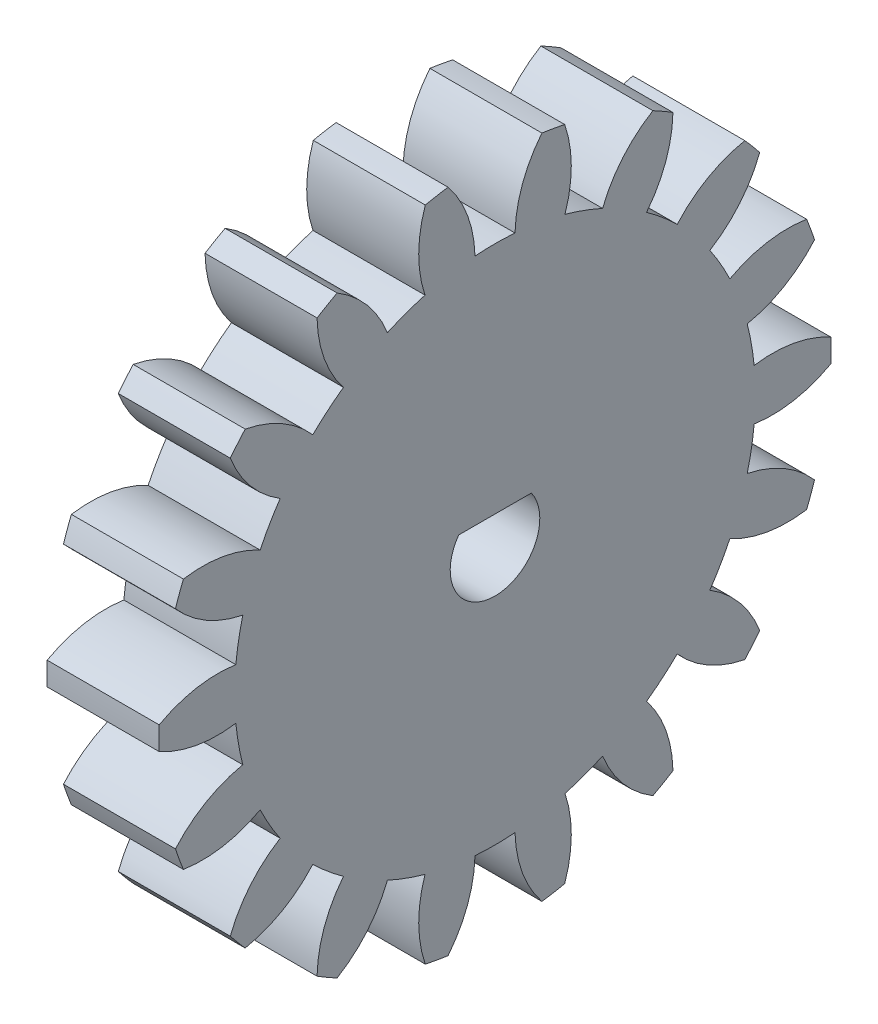
SolidWorks part; units mm, degrees
ref_plane "Plane1" through (0, 0, 0) normal (0, 0, 1) x (1, 0, 0)
ref_plane "Plane2" through (0, 0, 0) normal (0, 1, 0) x (1, 0, 0)
ref_plane "Plane3" through (0, 0, 0) normal (1, 0, 0) x (0, 0, -1)
sketch "HoldingSke" plane through (0, 0, 0) normal (0, 1, 0) x (1, 0, 0)
  line L0 (0, 0) -> (0.634, -0.206)
  line L1 (-15, 0) -> (100, 0) construction
  line L2 (0, 0) -> (-2.1039, 2.3779)
  line L3 (0, 0) -> (-11.863, 4.5341)
  line L4 (0, 0) -> (8.2133, 2.6687)
  line L5 (0, 0) -> (-46.8476, -17.4728)
  line L6 (0, 0) -> (-4.1448, -2.7965)
  line L7 (-2.1039, 2.3779) -> (8.6586, 51.2059)
  line L8 (-76.2, 54.61) -> (-76.1, 54.61)
  line L9 (-67.7845, 28.3722) -> (-49.3413, 33.142)
  line L10 (-76.2, 71.12) -> (104.1128, 71.12)
  line L11 (0, 0) -> (-5, 0)
  line L12 (-76.2, 101.6) -> (-76.147, 101.6)
  line L13 (24.9733, 27.94) -> (52.9518, 28.4284)
  line L14 (24.9733, 27.94) -> (24.9743, 27.94)
  line L15 (24.9733, 27.94) -> (100.4006, 29.5858)
  line L16 (-63.627, -1.5) -> (-12.827, -1.5)
  circle A0 centre (0, 0) radius 0.4
  circle A1 centre (0, 0) radius 11.624
  circle A2 centre (0, 0) radius 37.5
  circle A3 centre (0, 0) radius 0.4
  dimension "MHD" = 23.248
  dimension "Hub_dia" = 75
  dimension "Bore" = 0.8
  dimension "MBD" = 0.8
  dimension "Num_teeth" = 18
  dimension "Pitch" = 0.6667
  dimension "Overall_len" = 50
  dimension "Show_teeth" = 18
  dimension "Thickness" = 5
  dimension "OAL" = 50.0001
  dimension "T_dim" = 0.1
  dimension "Ap" = 14.5
  dimension "H" = 19.05
  dimension "Pitch_radius" = 180.3128
  dimension "Width" = 5
  dimension "Backlash" = 0.053
  dimension "Addendum_fac" = 1
  dimension "Dedendum_fac" = 1.25
  dimension "Clearance_fac" = 0.25
  dimension "Dedendum_add" = 0.001
  dimension "Module" = 1.5
sketch "BasProSke" plane through (0, 0, 0) normal (0, 1, 0) x (1, 0, 0)
  line L0 (-10, 0) -> (60, 0) construction
  line L1 (0, 0) -> (0, 15)
  line L2 (0, 0) -> (5, 0)
  line L3 (5, 0) -> (5, 15)
  line L4 (5, 15) -> (0, 15)
  dimension "Thickness" = 5
  dimension "Diameter" = 30
revolve "Base-Revolve" add sketch "BasProSke" angle 360 about L0
sketch "TooCutSke" plane through (0, 0, 0) normal (1, 0, 0) x (0, 0, -1)
  line L1 (0, 0) -> (0, 107) construction
  line L2 (0, 0) -> (-1.2693, 13.4402) construction
  line L3 (0, 0) -> (-4.6734, 26.504) construction
  line L4 (-1.2693, 13.4402) -> (-2.3367, 13.252) construction
  arc A0 (0.8932, 11.5896) -> (-0.8932, 11.5896) centre (0, 0) ccw
  arc A1 (2.1127, 14.8761) -> (-2.1127, 14.8761) centre (0, 0) ccw
  circle A2 centre (0, 0) radius 13.5 construction
  circle A3 centre (0, 0) radius 13.07 construction
  arc A4 (-0.8932, 11.5896) -> (-2.1127, 14.8761) centre (-6.2916, 11.456) ccw
  arc A5 (2.1127, 14.8761) -> (0.8932, 11.5896) centre (6.2916, 11.456) ccw
  dimension "Root_dia" = 23.248
  dimension "Overcut_dia" = 30.0508
  dimension "Pitch_dia" = 27
  dimension "Base_dia" = 26.14
  dimension "Flank_rad" = 5.4
  dimension "Half_ang" = 10
  dimension "Half_CT" = 1.0839
extrude "ToothCut" cut sketch "TooCutSke" along normal through all
fillet "Breaks" [suppressed] radius 0.03
fillet "RootFillets" [suppressed] radius 0.376
pattern_circular "TeethCuts" count 18 every 20 about axis through (-10, 0, 0) along (1, 0, 0) of "ToothCut", "RootFillets", "Breaks"
sketch "HubNeaOneSke" plane through (0, 0, 0) normal (-1, 0, 0) x (0, 0, 1)
  circle A0 centre (0, 0) radius 11.624
  dimension "Diameter" = 23.248
extrude "HubNearOne" [suppressed] add sketch "HubNeaOneSke" along normal blind 45.0001
sketch "HubNeaBotSke" plane through (0, 0, 0) normal (-1, 0, 0) x (0, 0, 1)
  circle A0 centre (0, 0) radius 11.624
  dimension "Diameter" = 23.248
extrude "HubNearBoth" [suppressed] add sketch "HubNeaBotSke" along normal blind 22.5
ref_plane "FarPln" through (5, 0, 0) normal (1, 0, 0) x (0, 0, -1)
sketch "HubFarSke" plane through (5, 0, 0) normal (1, 0, 0) x (0, 0, -1)
  circle A0 centre (0, 0) radius 11.624
  dimension "Diameter" = 23.248
extrude "HubFar" [suppressed] add sketch "HubFarSke" along normal blind 22.5
sketch "BorSke" plane through (0, 0, 0) normal (1, 0, 0) x (0, 0, -1)
  circle A0 centre (0, 0) radius 0.4
  dimension "Diameter" = 0.8
extrude "Bore" cut sketch "BorSke" along normal mid plane 100.0001
sketch "KeySke" plane through (0, 0, 0) normal (1, 0, 0) x (0, 0, -1)
  line L0 (-0.05, 0) -> (-0.05, 0.5)
  line L1 (-0.05, 0.5) -> (0.05, 0.5)
  line L2 (0.05, 0.5) -> (0.05, 0)
  line L3 (0, 0) -> (0, 34) construction
  line L4 (-0.05, 0) -> (0.05, 0)
  dimension "Offset" = 0.5
  dimension "Width" = 0.1
extrude "Keyway" [suppressed] cut sketch "KeySke" along normal mid plane 100.0001
pattern_circular "Keyway2" [suppressed] count 2 every 90 about axis through (-10, 0, 0) along (1, 0, 0)
sketch "Sketch1" plane through (5, 0, 0) normal (1, 0, 0) x (0, 0, -1)
  line L0 (-1.6209, 1.1716) -> (1.6209, 1.1716)
  circle A0 centre (0, 0) radius 2
extrude "Cut-Extrude1" cut sketch "Sketch1" against normal through all contours L0 A0
equation "' \"Module@HoldingSke\" = 6.35"
equation "' \"Num_teeth@HoldingSke\" = 12"
equation "' \"Ap@HoldingSke\" =  20"
equation "' \"Ap@HoldingSke\" = 20"
equation "' \"Width@HoldingSke\" = 0.5 * 25.4"
equation "' \"Hub_dia@HoldingSke\"= 1 * 25.4"
equation "' \"Hub_dia@HoldingSke\" = 1 * 25.4"
equation "' \"Overall_len@HoldingSke\" = 1.0 * 25.4"
equation "' \"Bore@HoldingSke\" = 0.75 * 25.4"
equation "' \"T_dim@HoldingSke\" = 0.1 * 25.4"
equation "' \"Width@KeySke\" = 0.25 * 25.4"
equation "' \"Show_teeth@HoldingSke\" = 13"
equation "' \"Backlash@HoldingSke\" = 0.009 * 25.4"
equation "' \"Addendum_fac@HoldingSke\" = 1.0"
equation "' \"Dedendum_fac@HoldingSke\" = 1.25"
equation "' \"Dedendum_add@HoldingSke\" = 0.00005 * 25.4"
equation "' \"Clearance_fac@HoldingSke\" = 0.25"
equation "\"Pitch@HoldingSke\" = 1 / \"Module@HoldingSke\""
equation "\"Overcut_dia@TooCutSke\" = (\"Num_teeth@HoldingSke\" + 2 * \"Addendum_fac@HoldingSke\") / \"Pitch@HoldingSke\" + 0.002 * 25.4"
equation "\"Pitch_dia@TooCutSke\" = \"Num_teeth@HoldingSke\" / \"Pitch@HoldingSke\""
equation "\"Base_dia@TooCutSke\" = \"Num_teeth@HoldingSke\" / \"Pitch@HoldingSke\" * cos((\"Ap@HoldingSke\"  * 3.14159265 / 180))"
equation "\"Root_dia@TooCutSke\" = (\"Num_teeth@HoldingSke\" + 2) / \"Pitch@HoldingSke\" - 2 * (\"Addendum_fac@HoldingSke\" + \"Dedendum_fac@HoldingSke\") / \"Pitch@HoldingSke\" - \"Dedendum_add@HoldingSke\" * 2"
equation "\"Half_ang@TooCutSke\" = 180 / \"Num_teeth@HoldingSke\""
equation "\"Half_CT@TooCutSke\" = \"Num_teeth@HoldingSke\" / \"Pitch@HoldingSke\" * sin((3.14159265 / 2 / \"Num_teeth@HoldingSke\")) / 2 - 7 * \"Backlash@HoldingSke\" / 4"
equation "\"Flank_rad@TooCutSke\" = \"Num_teeth@HoldingSke\" / \"Pitch@HoldingSke\" / 5"
equation "\"Radius@RootFillets\" = \"Clearance_fac@HoldingSke\" / \"Pitch@HoldingSke\" + \"Dedendum_add@HoldingSke\""
equation "\"Break_rad@Breaks\" = 0.02 / \"Pitch@HoldingSke\""
equation "\"Thickness@HoldingSke\" = \"Width@HoldingSke\""
equation "\"OAL@HoldingSke\" = \"Thickness@HoldingSke\""
equation "\"MHD@HoldingSke\" = (\"Num_teeth@HoldingSke\" + 2) / \"Pitch@HoldingSke\" - 2 * (\"Addendum_fac@HoldingSke\" + \"Dedendum_fac@HoldingSke\")  / \"Pitch@HoldingSke\" - \"Dedendum_add@HoldingSke\" * 2"
equation "\"MBD@HoldingSke\" = (\"Num_teeth@HoldingSke\" + 2) / \"Pitch@HoldingSke\" - 2 * (\"Addendum_fac@HoldingSke\" + \"Dedendum_fac@HoldingSke\")  / \"Pitch@HoldingSke\" - \"Dedendum_add@HoldingSke\" * 2 - 0.002 * 25.4"
equation "\"MHD@HoldingSke\" = ((sgn( \"MHD@HoldingSke\" - \"Hub_dia@HoldingSke\" )-1)*( \"MHD@HoldingSke\" - \"Hub_dia@HoldingSke\" ))/-2+ \"Hub_dia@HoldingSke\""
equation "\"MBD@HoldingSke\" = ((sgn( \"MBD@HoldingSke\" - \"Bore@HoldingSke\" )-1)*( \"MBD@HoldingSke\" - \"Bore@HoldingSke\" ))/-2+ \"Bore@HoldingSke\""
equation "\"OAL@HoldingSke\" = ((sgn( \"OAL@HoldingSke\" - \"Overall_len@HoldingSke\" )+1)*( \"OAL@HoldingSke\" - \"Overall_len@HoldingSke\" ))/2 + \"Overall_len@HoldingSke\" + 0.000002 * 25.4"
equation "\"Num_teeth@TeethCuts\" = int( \"Show_teeth@HoldingSke\" ) + 1"
equation "\"Num_teeth@TeethCuts\" = ((sgn( \"Num_teeth@TeethCuts\" - \"Num_teeth@HoldingSke\" )-1)*( \"Num_teeth@TeethCuts\" - \"Num_teeth@HoldingSke\" ))/-2+ \"Num_teeth@HoldingSke\""
equation "\"Num_teeth@TeethCuts\" = ((sgn( \"Num_teeth@TeethCuts\" - 2.0)+1)*( \"Num_teeth@TeethCuts\" - 2.0))/2 +2.0"
equation "\"Angle@TeethCuts\" = 360.0 / \"Num_teeth@HoldingSke\""
equation "\"Diameter@BasProSke\" = (\"Num_teeth@HoldingSke\" + 2 * \"Addendum_fac@HoldingSke\") / \"Pitch@HoldingSke\""
equation "\"Thickness@BasProSke\"  = \"Thickness@HoldingSke\""
equation "' \"Fillet_rad@BasProSke\" =  \"Thickness@HoldingSke\" * 0.05"
equation "' \"Fillet_rad@BasProSke\" = \"Thickness@HoldingSke\" * 0.05"
equation "\"MHD@HoldingSke\" = ((sgn( \"MHD@HoldingSke\" - \"Root_dia@TooCutSke\" )-1)*( \"MHD@HoldingSke\" - \"Root_dia@TooCutSke\" ))/-2+ \"Root_dia@TooCutSke\""
equation "\"Diameter@HubNeaOneSke\" = \"MHD@HoldingSke\""
equation "\"Length@HubNearOne\" = \"OAL@HoldingSke\" - \"Thickness@BasProSke\""
equation "\"Diameter@HubNeaBotSke\" = \"MHD@HoldingSke\""
equation "\"Length@HubNearBoth\" = ( \"OAL@HoldingSke\" - \"Thickness@BasProSke\" ) / 2.0"
equation "\"Thickness@FarPln\" = \"Thickness@BasProSke\""
equation "\"Diameter@HubFarSke\" = \"MHD@HoldingSke\""
equation "\"Length@HubFar\" = ( \"OAL@HoldingSke\" - \"Thickness@BasProSke\" ) / 2.0"
equation "\"Diameter@BorSke\" = \"MBD@HoldingSke\""
equation "\"D1@Bore\" = \"OAL@HoldingSke\" * 2.0"
equation "\"D1@Keyway\" = \"OAL@HoldingSke\" * 2.0"
equation "\"Offset@KeySke\" = \"T_dim@HoldingSke\" + \"MBD@HoldingSke\" / 2.0"
